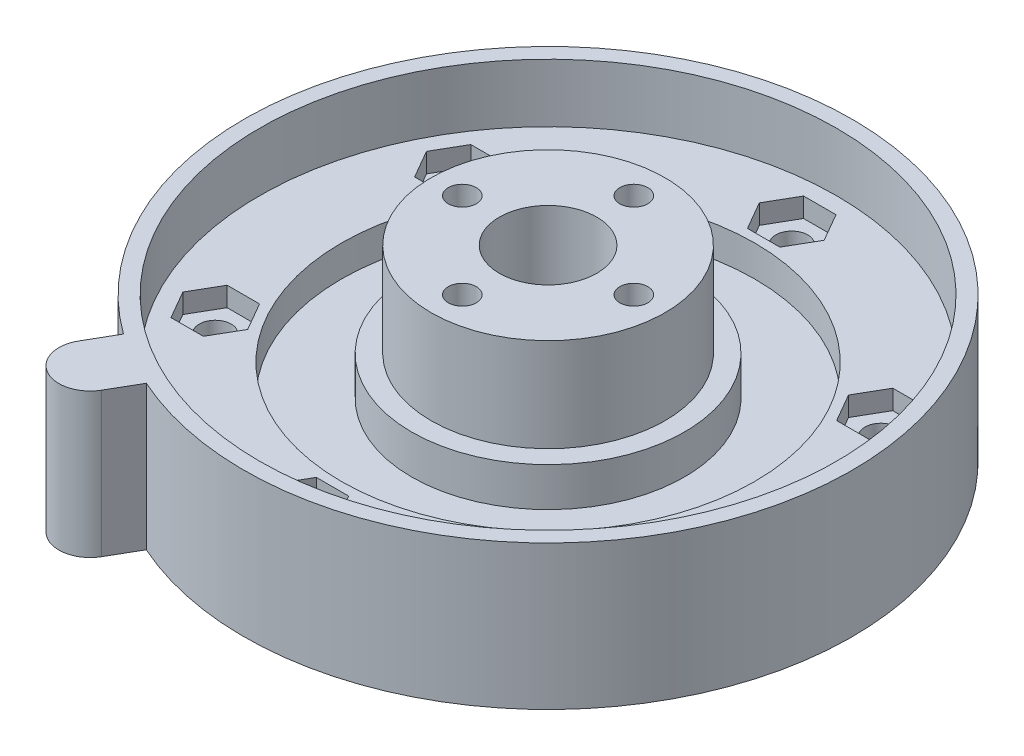
SolidWorks part; units mm, degrees
ref_plane "Front Plane" through (0, 0, 0) normal (0, 0, 1) x (1, 0, 0)
ref_plane "Top Plane" through (0, 0, 0) normal (0, 1, 0) x (1, 0, 0)
ref_plane "Right Plane" through (0, 0, 0) normal (1, 0, 0) x (0, 0, -1)
sketch "Sketch1" plane through (0, 0, 0) normal (0, 1, 0) x (1, 0, 0)
  circle A0 centre (0, 0) radius 39
  dimension "D1" = 78
extrude "Boss-Extrude1" add sketch "Sketch1" along normal blind 18.5
sketch "Sketch2" plane through (0, 18.5, 0) normal (0, 1, 0) x (1, 0, 0)
  circle A2 centre (0, 0) radius 37
  circle A3 centre (0, 0) radius 37
  dimension "D1" = 2
extrude "Cut-Extrude1" cut sketch "Sketch2" against normal blind 7.5
sketch "Sketch3" plane through (0, 11, 0) normal (0, 1, 0) x (1, 0, 0)
  circle A0 centre (0, 0) radius 26.5
  dimension "D1" = 53
extrude "Cut-Extrude2" cut sketch "Sketch3" against normal blind 4
sketch "Sketch4" plane through (0, 7, 0) normal (0, 1, 0) x (1, 0, 0)
  circle A0 centre (0, 0) radius 17.5
  dimension "D1" = 35
extrude "Boss-Extrude2" add sketch "Sketch4" along normal blind 5
sketch "Sketch5" plane through (0, 12, 0) normal (0, 1, 0) x (1, 0, 0)
  circle A0 centre (0, 0) radius 15
  dimension "D1" = 30
extrude "Boss-Extrude3" add sketch "Sketch5" along normal blind 12
sketch "Sketch6" plane through (0, 24, 0) normal (0, 1, 0) x (1, 0, 0)
  circle A0 centre (0, 0) radius 6.25
  circle A1 centre (0, 11) radius 1.8
  circle A2 centre (11, 0) radius 1.8
  circle A3 centre (0, -11) radius 1.8
  circle A4 centre (-11, 0) radius 1.8
  point P5 (0, 0)
  dimension "D1" = 12.5
  dimension "D2" = 3.6
  dimension "D3" = 11
  dimension "D4" = 4
extrude "Cut-Extrude3" cut sketch "Sketch6" against normal through all
hole_wizard "CSK for M4 Countersunk Flat Head Screw1" positions "3DSketch1" profile "Sketch8" countersink size "M4" standard "ISO" end condition through all
sketch3d "3DSketch1"
  line L0 (0, 0, 11) -> (0, 24, 11) construction
  line L1 (11, 0, 0) -> (11, 24, 0) construction
  line L2 (0, 0, -11) -> (0, 24, -11) construction
  line L3 (-11, 0, 0) -> (-11, 24, 0) construction
  point P0 (0, 0, 11)
  point P4 (11, 0, 0)
  point P8 (0, 0, -11)
  point P12 (-11, 0, 0)
sketch "Sketch8" plane through (0, 0, 11) normal (1, 0, 0) x (0, 0, -1)
  line L0 (0, 0) -> (0, 24)
  line L1 (0, 24) -> (1.75, 24)
  line L2 (1.75, 24) -> (1.75, 2.8)
  line L3 (1.75, 2.8) -> (4.55, 0)
  line L5 (4.55, 0) -> (0, 0)
  line L6 (-1.75, 2.8) -> (-4.55, 0) construction
  line L11 (0, -6.35) -> (0, 107.95) construction
  dimension "Thru Hole Dia." = 3.5
  dimension "Thru Hole Depth" = 24
  dimension "Near C'Sink Dia." = 9.1
  dimension "Near C'Sink Angle" = 90
sketch "Sketch9" plane through (0, 11, 0) normal (0, 1, 0) x (1, 0, 0)
  circle A0 centre (0, 31.25) radius 2.05
  circle A1 centre (27.0633, 15.625) radius 2.05
  circle A2 centre (27.0633, -15.625) radius 2.05
  circle A3 centre (0, -31.25) radius 2.05
  circle A4 centre (-27.0633, -15.625) radius 2.05
  circle A5 centre (-27.0633, 15.625) radius 2.05
  dimension "D2" = 4.1
  dimension "D1" = 31.25
  dimension "D3" = 6
extrude "Cut-Extrude4" cut sketch "Sketch9" against normal through all
sketch "Sketch10" plane through (0, 11, 0) normal (0, 1, 0) x (1, 0, 0)
  line L1 (2.0785, 34.85) -> (-2.0785, 34.85)
  line L2 (-2.0785, 34.85) -> (-4.1569, 31.25)
  line L3 (-4.1569, 31.25) -> (-2.0785, 27.65)
  line L4 (-2.0785, 27.65) -> (2.0785, 27.65)
  line L5 (2.0785, 27.65) -> (4.1569, 31.25)
  line L6 (4.1569, 31.25) -> (2.0785, 34.85)
  circle A0 centre (0, 31.25) radius 3.6 construction
  point P1 (0, 0)
  dimension "D1" = 7.2
extrude "Cut-Extrude5" cut sketch "Sketch10" against normal blind 2.5
pattern_circular "CirPattern1" count 6 over 360 about axis through (0, 0, 0) along (0, 1, 0) of "Cut-Extrude5"
sketch "Sketch11" plane through (0, 18.5, 0) normal (0, 1, 0) x (1, 0, 0)
  line L0 (-21.5, -37.2391) -> (0, 0) construction
  line L1 (0, 0) -> (0, -39) construction
  line L2 (-18.0359, -39.2391) -> (-15.9331, -35.5969)
  line L3 (-24.9641, -35.2391) -> (-22.8613, -31.5969)
  line L4 (0, -8) -> (3.4641, -2)
  line L5 (-18.0359, -39.2391) -> (3.4641, -2) construction
  line L6 (-24.9641, -35.2391) -> (-3.4641, 2) construction
  circle A0 centre (-21.5, -37.2391) radius 4
  circle A1 centre (0, 0) radius 39 construction
  circle A2 centre (0, 0) radius 39
  circle M5 centre (0, 0) radius 39
  dimension "D3" = 8
  dimension "D1" = 30
  dimension "D2" = 43
  dimension "D4" = 4
  dimension "D5" = 4
extrude "Boss-Extrude5" add sketch "Sketch11" against normal through all contours A0 | A0 L2 M5 | A0 L3 M5
